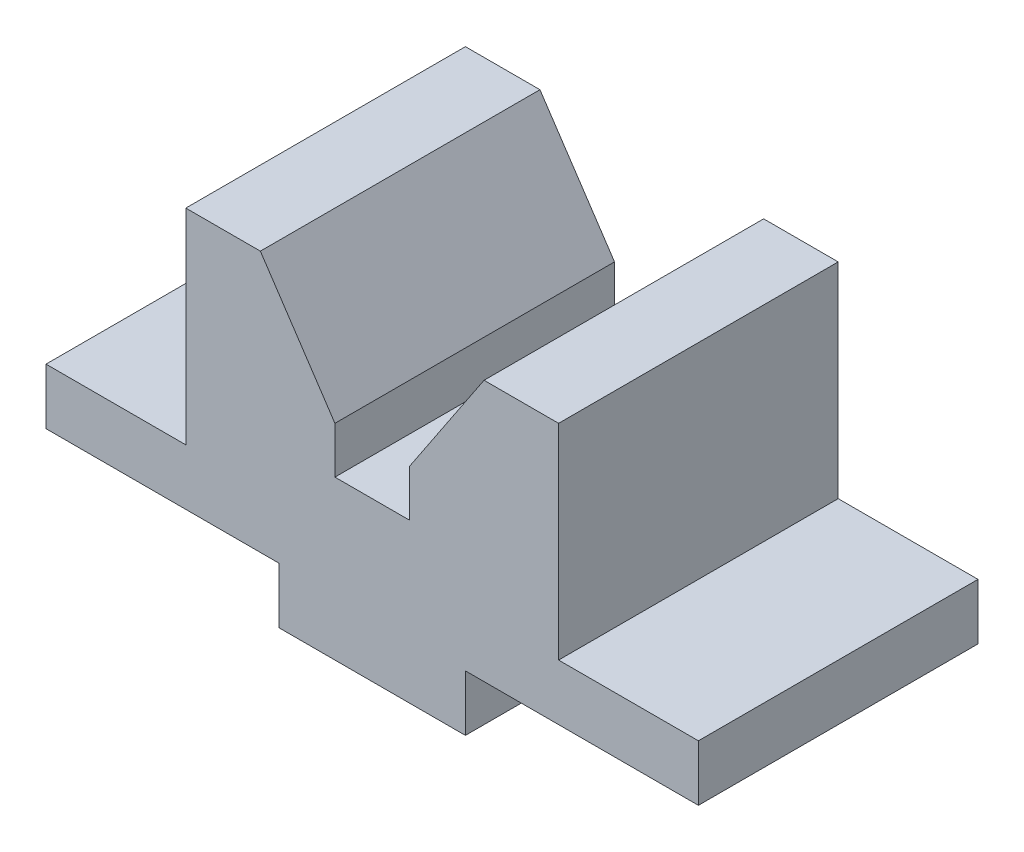
SolidWorks part; units mm, degrees
ref_plane "Front Plane" through (0, 0, 0) normal (0, 0, 1) x (1, 0, 0)
ref_plane "Top Plane" through (0, 0, 0) normal (0, 1, 0) x (1, 0, 0)
ref_plane "Right Plane" through (0, 0, 0) normal (1, 0, 0) x (0, 0, -1)
sketch "Sketch1" plane through (0, 0, 0) normal (0, 0, 1) x (1, 0, 0)
  line L0 (0, 0) -> (0, -68045.0995) construction
  line L1 (0, 0) -> (68045.0995, 0) construction
  line L2 (-10, 0) -> (10, 0)
  line L3 (10, 0) -> (10, 6)
  line L4 (10, 6) -> (35, 6)
  line L5 (35, 6) -> (35, 12)
  line L6 (35, 12) -> (20, 12)
  line L7 (20, 12) -> (20, 34)
  line L8 (20, 34) -> (12, 34)
  line L9 (12, 34) -> (4, 22)
  line L10 (4, 22) -> (4, 17)
  line L11 (-4, 22) -> (-4, 17)
  line L12 (-12, 34) -> (-4, 22)
  line L13 (-20, 34) -> (-12, 34)
  line L14 (-20, 12) -> (-20, 34)
  line L15 (-35, 12) -> (-20, 12)
  line L16 (-35, 6) -> (-35, 12)
  line L17 (-10, 6) -> (-35, 6)
  line L18 (-10, 0) -> (-10, 6)
  line L19 (-4, 17) -> (4, 17)
  point P8 (0, 0)
  dimension "D1" = 70
  dimension "D2" = 20
  dimension "D3" = 6
  dimension "D4" = 8
  dimension "D5" = 8
  dimension "D6" = 15
  dimension "D7" = 12
  dimension "D8" = 5
  dimension "D9" = 34
extrude "Boss-Extrude1" add sketch "Sketch1" along normal mid plane 30
